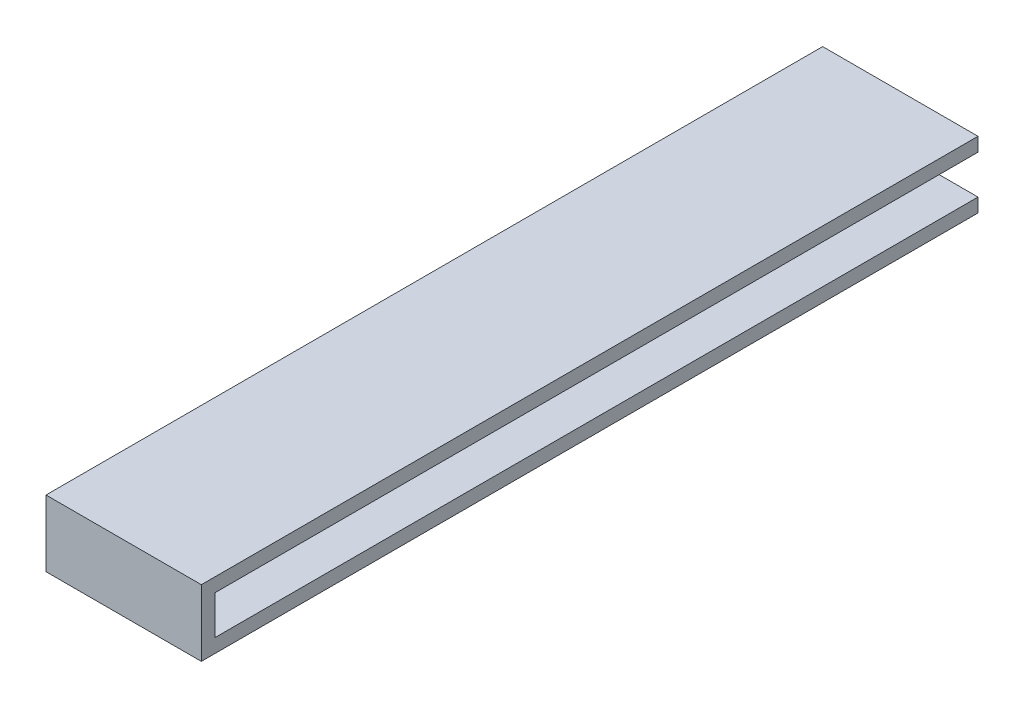
SolidWorks part; units mm, degrees
ref_plane "Front Plane" through (0, 0, 0) normal (0, 0, 1) x (1, 0, 0)
ref_plane "Top Plane" through (0, 0, 0) normal (0, 1, 0) x (1, 0, 0)
ref_plane "Right Plane" through (0, 0, 0) normal (1, 0, 0) x (0, 0, -1)
sketch "Sketch1" plane through (0, 0, 0) normal (0, 1, 0) x (1, 0, 0)
  line L1 (0, 0) -> (-0.4, 0)
  line L2 (0, 0) -> (0, 2)
  line L3 (0, 2) -> (-0.4, 2)
  line L4 (-0.4, 0) -> (-0.4, 2)
  dimension "D1" = 0.4
  dimension "D2" = 2
extrude "Boss-Extrude2" add sketch "Sketch1" along normal blind 0.0356
sketch "Sketch2" plane through (0, 0.0356, 0) normal (0, 1, 0) x (1, 0, 0)
  line L0 (-0.4, 2) -> (-0.4, 0) construction
  line L1 (0, 0) -> (-0.4, 0)
  line L2 (0, 0) -> (0, 0.0356)
  line L3 (0, 0.0356) -> (-0.4, 0.0356)
  line L4 (-0.4, 0) -> (-0.4, 0.0356)
  dimension "D1" = 0.0356
extrude "Boss-Extrude3" add sketch "Sketch2" along normal blind 0.1356
sketch "Sketch4" plane through (0, 0, -0.0356) normal (0, 0, -1) x (-1, 0, 0)
  line L0 (0.4, 0.1711) -> (0.4, 0.0356) construction
  line L1 (0, 0.1711) -> (0.4, 0.1711)
  line L2 (0, 0.1711) -> (0, 0.1356)
  line L3 (0, 0.1356) -> (0.4, 0.1356)
  line L4 (0.4, 0.1711) -> (0.4, 0.1356)
  dimension "D1" = 0.0356
extrude "Boss-Extrude4" add sketch "Sketch4" along normal blind 1.9644
